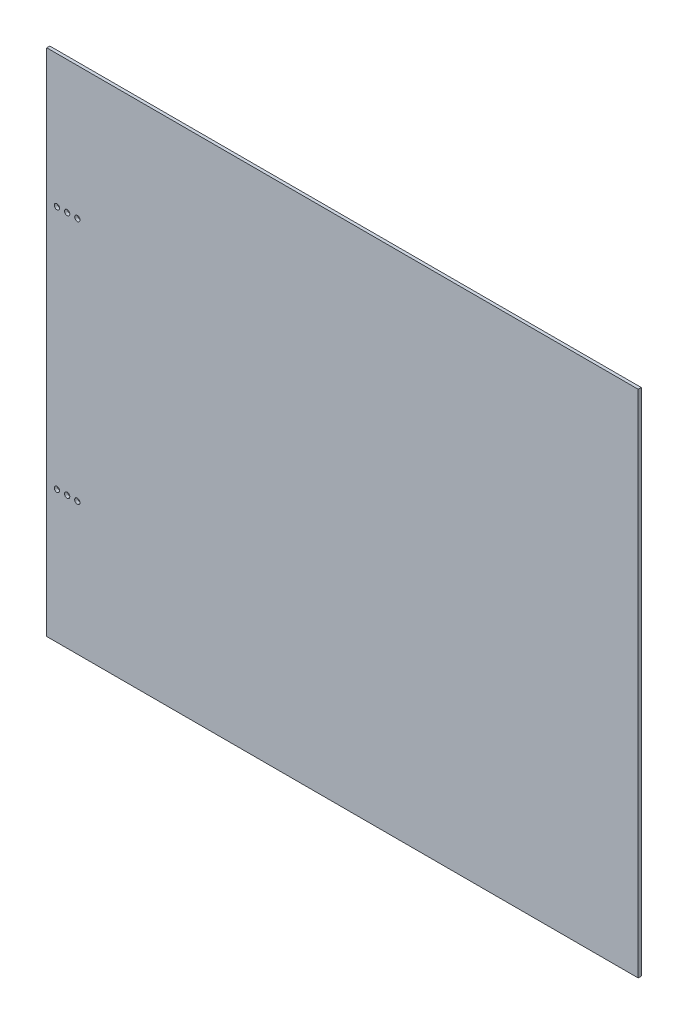
SolidWorks part; units mm, degrees
ref_plane "前视基准面" through (0, 0, 0) normal (0, 0, 1) x (1, 0, 0)
ref_plane "上视基准面" through (0, 0, 0) normal (0, 1, 0) x (1, 0, 0)
ref_plane "右视基准面" through (0, 0, 0) normal (1, 0, 0) x (0, 0, -1)
sketch "草图1" plane through (0, 0, 0) normal (0, 0, 1) x (1, 0, 0)
  line L1 (0, 0) -> (580, 0)
  line L2 (0, 0) -> (0, 500)
  line L3 (0, 500) -> (580, 500)
  line L4 (580, 0) -> (580, 500)
  circle A0 centre (10, 370) radius 2.6
  circle A1 centre (10, 130) radius 2.6
  circle A2 centre (20, 130) radius 2.6
  circle A3 centre (20, 370) radius 2.6
  circle A4 centre (30, 130) radius 2.6
  circle A5 centre (30, 370) radius 2.6
  dimension "D3" = 5.2
  dimension "D4" = 5.2
  dimension "D1" = 580
  dimension "D2" = 500
  dimension "D5" = 130
  dimension "D6" = 130
  dimension "D7" = 10
  dimension "D8" = 10
  dimension "D9" = 3
extrude "凸台-拉伸1" add sketch "草图1" along normal blind 3
